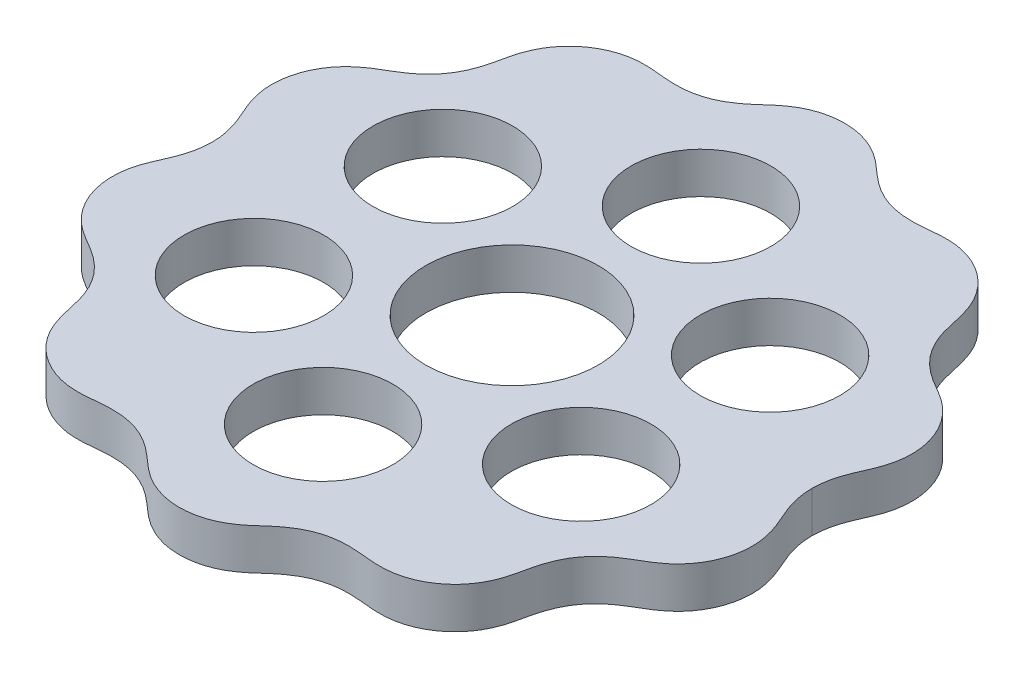
SolidWorks part; units mm, degrees
ref_plane "Front Plane" through (0, 0, 0) normal (0, 0, 1) x (1, 0, 0)
ref_plane "Top Plane" through (0, 0, 0) normal (0, 1, 0) x (1, 0, 0)
ref_plane "Right Plane" through (0, 0, 0) normal (1, 0, 0) x (0, 0, -1)
sketch "Sketch1" plane through (0, 0, 0) normal (0, 1, 0) x (1, 0, 0)
  circle A0 centre (0, 0) radius 10.5
  circle A1 centre (0, 0) radius 23 construction
  circle A2 centre (0, 23) radius 8.5
  circle A3 centre (19.9186, 11.5) radius 8.5
  circle A4 centre (19.9186, -11.5) radius 8.5
  circle A5 centre (0, -23) radius 8.5
  circle A6 centre (-19.9186, -11.5) radius 8.5
  circle A7 centre (-19.9186, 11.5) radius 8.5
  spline S0 degree 4 poles (38.858, 11.0852) (38.9322, 10.6047) (39.0099, 9.6527) (38.9421, 8.4984) (38.6357, 7.1878) (38.2864, 6.1974) (37.9882, 5.4798) (37.683, 4.7937) (37.3957, 4.1278) (37.1411, 3.4761) (36.9534, 2.9172) (36.8163, 2.4305) (36.7119, 1.9894) (36.6343, 1.5942) (36.5778, 1.2237) (36.5395, 0.8732) (36.5195, 0.614) (36.5099, 0.4402) (36.5043, 0.2856) (36.5014, 0.1595) (36.4995, 0.0195) (36.5002, -0.1092) (36.5052, -0.3492) (36.5165, -0.5716) (36.5378, -0.8544) (36.5744, -1.1968) (36.6281, -1.557) (36.7013, -1.9382) (36.7805, -2.282) (36.8613, -2.59) (36.9736, -2.9718) (37.1249, -3.4249) (37.3351, -3.9789) (37.6108, -4.6305) (37.913, -5.3088) (38.218, -6.0248) (38.5793, -7.0007) (38.9036, -8.2662) (39.0404, -9.8358) (38.8332, -11.6193) (38.3001, -13.2875) (37.487, -14.7883) (36.5194, -15.9854) (35.4632, -16.9217) (34.4806, -17.5844) (33.652, -18.0704) (32.7414, -18.5999) (31.7458, -19.2304) (30.6441, -20.104) (29.5519, -21.317) (28.7099, -22.6884) (28.1292, -24.1273) (27.764, -25.5368) (27.4986, -26.872) (27.1446, -28.2457) (26.5859, -29.6132) (25.7538, -30.9467) (24.6303, -32.1739) (23.3041, -33.1785) (21.8187, -33.928) (20.3544, -34.3562) (18.98, -34.5225) (17.8101, -34.5087) (16.8566, -34.4266) (15.9782, -34.3339) (15.1709, -34.2657) (14.1498, -34.2296) (12.9163, -34.2978) (11.4927, -34.5814) (10.0187, -35.1679) (8.7307, -35.9469) (7.6167, -36.8334) (6.6277, -37.7411) (5.5491, -38.6675) (4.2889, -39.4888) (2.8327, -40.1155) (1.2099, -40.4828) (-0.4524, -40.5514) (-2.1, -40.32) (-3.516, -39.8474) (-4.6848, -39.2366) (-5.5951, -38.6033) (-6.2913, -38.0314) (-6.9352, -37.4556) (-7.5529, -36.9053) (-8.3721, -36.2275) (-9.4173, -35.5016) (-10.7447, -34.8354) (-12.2749, -34.3962) (-13.5683, -34.2461) (-14.6093, -34.2407) (-15.4184, -34.2856) (-16.0966, -34.3467) (-16.984, -34.439) (-18.1297, -34.5342) (-19.5142, -34.4997) (-21.1001, -34.1777) (-22.6427, -33.5543) (-24.0472, -32.6623) (-25.2685, -31.5325) (-26.1543, -30.3477) (-26.7561, -29.2048) (-27.1372, -28.1922) (-27.3763, -27.3513) (-27.5642, -26.522) (-27.7363, -25.7129) (-27.9936, -24.6343) (-28.3991, -23.3794) (-29.0768, -22.0048) (-30.0541, -20.7188) (-31.0788, -19.746) (-32.0395, -19.0415) (-32.8641, -18.528) (-33.7908, -17.9899) (-34.8204, -17.3824) (-35.9613, -16.5376) (-37.0866, -15.3426) (-37.9865, -13.9433) (-38.6185, -12.4041) (-38.9637, -10.7767) (-39.0028, -9.321) (-38.8449, -8.0857) (-38.5926, -7.0813) (-38.3262, -6.297) (-38.0113, -5.5316) (-37.6749, -4.7759) (-37.3784, -4.0878) (-37.1368, -3.4613) (-36.9489, -2.8982) (-36.8252, -2.4645) (-36.7344, -2.0886) (-36.6616, -1.735) (-36.6042, -1.4037) (-36.5611, -1.0845) (-36.531, -0.7734) (-36.5136, -0.5202) (-36.5043, -0.3098) (-36.4995, -0.0654) (-36.4997, 0.0863) (-36.5054, 0.3578) (-36.5173, 0.5838) (-36.5395, 0.8738) (-36.5778, 1.2233) (-36.6343, 1.5944) (-36.7119, 1.9893) (-36.7969, 2.3486) (-36.8848, 2.6739) (-37.007, 3.0768) (-37.1717, 3.5546) (-37.3957, 4.1277) (-37.683, 4.7937) (-37.9882, 5.4798) (-38.2864, 6.1974) (-38.6357, 7.1878) (-38.9421, 8.4984) (-39.0099, 9.6527) (-38.9322, 10.6047) (-38.858, 11.0852) knots 0 0 0 0 0 0.01275 0.024998 0.030092 0.035186 0.04028 0.045374 0.049791 0.054208 0.058625 0.060834 0.063042 0.066105 0.069167 0.070698 0.07223 0.072995 0.073761 0.074526 0.075292 0.07679 0.078287 0.079785 0.081283 0.084278 0.087273 0.089361 0.091448 0.093536 0.095623 0.099798 0.103973 0.109075 0.114177 0.119279 0.124381 0.136358 0.148337 0.160314 0.171165 0.182016 0.192867 0.200455 0.208044 0.213054 0.218064 0.228085 0.238937 0.249793 0.260646 0.270064 0.279482 0.287924 0.296367 0.307217 0.318067 0.328918 0.339769 0.350619 0.36147 0.368707 0.375944 0.381255 0.386566 0.391878 0.397189 0.408044 0.418897 0.42975 0.438567 0.447383 0.456177 0.464971 0.475821 0.486672 0.497522 0.508373 0.519224 0.530074 0.536458 0.542842 0.548267 0.553691 0.559116 0.564541 0.576146 0.587 0.597853 0.606066 0.610172 0.614279 0.619103 0.623927 0.633575 0.644425 0.655276 0.666126 0.676977 0.687828 0.698679 0.70471 0.710741 0.716165 0.721589 0.727013 0.732437 0.74525 0.756105 0.766961 0.77457 0.782178 0.787304 0.792429 0.80268 0.813531 0.824381 0.835231 0.846082 0.856933 0.867783 0.873212 0.878641 0.884065 0.889489 0.894913 0.900338 0.903717 0.907097 0.910477 0.912166 0.913856 0.916569 0.919282 0.920639 0.921995 0.923352 0.924708 0.926239 0.92777 0.929302 0.930833 0.933895 0.936958 0.939166 0.941375 0.943584 0.945792 0.950209 0.954626 0.95972 0.964814 0.969908 0.975002 0.98725 1 1 1 1 1 construction
  spline S1 degree 4 poles (36.5, 0) (36.5, -0.0485) (36.5009, -0.1441) (36.5052, -0.3492) (36.5165, -0.5716) (36.5378, -0.8544) (36.5744, -1.1968) (36.6281, -1.557) (36.7013, -1.9382) (36.7805, -2.282) (36.8613, -2.59) (36.9736, -2.9718) (37.1249, -3.4249) (37.3351, -3.9789) (37.6108, -4.6305) (37.913, -5.3088) (38.218, -6.0248) (38.5793, -7.0007) (38.9036, -8.2662) (39.0404, -9.8358) (38.8332, -11.6193) (38.3001, -13.2875) (37.487, -14.7883) (36.5194, -15.9854) (35.4632, -16.9217) (34.4806, -17.5844) (33.652, -18.0704) (32.7414, -18.5999) (31.7458, -19.2304) (30.6441, -20.104) (29.5519, -21.317) (28.7099, -22.6884) (28.1292, -24.1273) (27.764, -25.5368) (27.4986, -26.872) (27.1446, -28.2457) (26.5859, -29.6132) (25.7538, -30.9467) (24.6303, -32.1739) (23.3041, -33.1785) (21.8187, -33.928) (20.3544, -34.3562) (18.98, -34.5225) (17.8101, -34.5087) (16.8566, -34.4266) (15.9782, -34.3339) (15.1709, -34.2657) (14.1498, -34.2296) (12.9163, -34.2978) (11.4927, -34.5814) (10.0187, -35.1679) (8.7307, -35.9469) (7.6167, -36.8334) (6.6277, -37.7411) (5.5491, -38.6675) (4.2889, -39.4888) (2.8327, -40.1155) (1.2099, -40.4828) (-0.4524, -40.5514) (-2.1, -40.32) (-3.516, -39.8474) (-4.6848, -39.2366) (-5.5951, -38.6033) (-6.2913, -38.0314) (-6.9352, -37.4556) (-7.5529, -36.9053) (-8.3721, -36.2275) (-9.4173, -35.5016) (-10.7447, -34.8354) (-12.2749, -34.3962) (-13.5683, -34.2461) (-14.6093, -34.2407) (-15.4184, -34.2856) (-16.0966, -34.3467) (-16.984, -34.439) (-18.1297, -34.5342) (-19.5142, -34.4997) (-21.1001, -34.1777) (-22.6427, -33.5543) (-24.0472, -32.6623) (-25.2685, -31.5325) (-26.1543, -30.3477) (-26.7561, -29.2048) (-27.1372, -28.1922) (-27.3763, -27.3513) (-27.5642, -26.522) (-27.7363, -25.7129) (-27.9936, -24.6343) (-28.3991, -23.3794) (-29.0768, -22.0048) (-30.0541, -20.7188) (-31.0788, -19.746) (-32.0395, -19.0415) (-32.8641, -18.528) (-33.7908, -17.9899) (-34.8204, -17.3824) (-35.9613, -16.5376) (-37.0866, -15.3426) (-37.9865, -13.9433) (-38.6185, -12.4041) (-38.9637, -10.7767) (-39.0028, -9.321) (-38.8449, -8.0857) (-38.5926, -7.0813) (-38.3262, -6.297) (-38.0113, -5.5316) (-37.6749, -4.7759) (-37.3784, -4.0878) (-37.1368, -3.4613) (-36.9489, -2.8982) (-36.8252, -2.4645) (-36.7344, -2.0886) (-36.6616, -1.735) (-36.6042, -1.4037) (-36.5611, -1.0845) (-36.531, -0.7734) (-36.5136, -0.5202) (-36.5043, -0.3098) (-36.5008, -0.1322) (-36.5, -0.0439) (-36.5, 0) knots 0.075292 0.075292 0.075292 0.075292 0.075292 0.07679 0.078287 0.079785 0.081283 0.084278 0.087273 0.089361 0.091448 0.093536 0.095623 0.099798 0.103973 0.109075 0.114177 0.119279 0.124381 0.136358 0.148337 0.160314 0.171165 0.182016 0.192867 0.200455 0.208044 0.213054 0.218064 0.228085 0.238937 0.249793 0.260646 0.270064 0.279482 0.287924 0.296367 0.307217 0.318067 0.328918 0.339769 0.350619 0.36147 0.368707 0.375944 0.381255 0.386566 0.391878 0.397189 0.408044 0.418897 0.42975 0.438567 0.447383 0.456177 0.464971 0.475821 0.486672 0.497522 0.508373 0.519224 0.530074 0.536458 0.542842 0.548267 0.553691 0.559116 0.564541 0.576146 0.587 0.597853 0.606066 0.610172 0.614279 0.619103 0.623927 0.633575 0.644425 0.655276 0.666126 0.676977 0.687828 0.698679 0.70471 0.710741 0.716165 0.721589 0.727013 0.732437 0.74525 0.756105 0.766961 0.77457 0.782178 0.787304 0.792429 0.80268 0.813531 0.824381 0.835231 0.846082 0.856933 0.867783 0.873212 0.878641 0.884065 0.889489 0.894913 0.900338 0.903717 0.907097 0.910477 0.912166 0.913856 0.916569 0.919282 0.920639 0.921995 0.923352 0.924708 0.924708 0.924708 0.924708 0.924708
  spline S2 degree 4 poles (-38.858, -11.0852) (-38.9322, -10.6047) (-39.0099, -9.6527) (-38.9421, -8.4984) (-38.6357, -7.1878) (-38.2864, -6.1974) (-37.9882, -5.4798) (-37.683, -4.7937) (-37.3957, -4.1277) (-37.1717, -3.5546) (-37.007, -3.0768) (-36.8848, -2.6739) (-36.7969, -2.3487) (-36.7119, -1.9892) (-36.6456, -1.652) (-36.5953, -1.3382) (-36.5586, -1.0489) (-36.535, -0.8153) (-36.5195, -0.614) (-36.5099, -0.4403) (-36.5043, -0.2858) (-36.5014, -0.1597) (-36.4995, -0.0193) (-36.5001, 0.0875) (-36.5031, 0.2488) (-36.5095, 0.4308) (-36.5187, 0.6009) (-36.5378, 0.8538) (-36.5744, 1.1972) (-36.6281, 1.5568) (-36.7013, 1.9383) (-36.7983, 2.3595) (-36.9244, 2.8204) (-37.0966, 3.3504) (-37.3351, 3.9789) (-37.6108, 4.6304) (-37.913, 5.3088) (-38.218, 6.0248) (-38.5793, 7.0007) (-38.9036, 8.2662) (-39.0404, 9.8358) (-38.8332, 11.6193) (-38.3001, 13.2875) (-37.487, 14.7883) (-36.5194, 15.9854) (-35.4632, 16.9217) (-34.4806, 17.5844) (-33.652, 18.0704) (-32.9065, 18.5039) (-32.257, 18.9066) (-31.4454, 19.4687) (-30.5156, 20.2467) (-29.5519, 21.317) (-28.7099, 22.6884) (-28.1292, 24.1273) (-27.764, 25.5368) (-27.4986, 26.872) (-27.1446, 28.2457) (-26.5859, 29.6132) (-25.7538, 30.9467) (-24.6303, 32.1739) (-23.3041, 33.1785) (-21.8187, 33.928) (-20.3544, 34.3562) (-18.98, 34.5225) (-17.8101, 34.5087) (-16.8566, 34.4266) (-15.9782, 34.3339) (-15.1709, 34.2657) (-14.1498, 34.2296) (-12.9163, 34.2978) (-11.4927, 34.5814) (-10.0187, 35.1679) (-8.7307, 35.9469) (-7.6167, 36.8334) (-6.6277, 37.7411) (-5.5491, 38.6675) (-4.2889, 39.4888) (-2.8327, 40.1155) (-1.2099, 40.4828) (0.4524, 40.5514) (2.1, 40.32) (3.516, 39.8474) (4.6848, 39.2366) (5.5951, 38.6033) (6.2913, 38.0314) (6.9352, 37.4556) (7.5529, 36.9053) (8.3721, 36.2275) (9.4173, 35.5016) (10.7447, 34.8354) (12.2749, 34.3962) (13.5683, 34.2461) (14.6093, 34.2407) (15.4184, 34.2856) (16.0966, 34.3467) (16.984, 34.439) (18.1297, 34.5342) (19.5142, 34.4997) (21.1001, 34.1777) (22.6427, 33.5543) (24.0472, 32.6623) (25.2685, 31.5325) (26.1543, 30.3477) (26.7561, 29.2048) (27.1372, 28.1922) (27.3763, 27.3513) (27.5642, 26.522) (27.7363, 25.7129) (27.9936, 24.6343) (28.3991, 23.3794) (29.0768, 22.0048) (30.0541, 20.7188) (31.0788, 19.746) (32.0395, 19.0415) (32.8641, 18.528) (33.7908, 17.9899) (34.8204, 17.3824) (35.9613, 16.5376) (37.0866, 15.3426) (37.9865, 13.9433) (38.6185, 12.4041) (38.9637, 10.7767) (39.0028, 9.321) (38.8449, 8.0857) (38.5926, 7.0813) (38.3262, 6.297) (38.0113, 5.5316) (37.6749, 4.7759) (37.3784, 4.0878) (37.1368, 3.4612) (36.9693, 2.9594) (36.8606, 2.5884) (36.7798, 2.2765) (36.7214, 2.0254) (36.6616, 1.735) (36.6042, 1.4036) (36.5611, 1.0847) (36.531, 0.7731) (36.5153, 0.5458) (36.5078, 0.3885) (36.5025, 0.222) (36.5, 0.0774) (36.4996, -0.0243) (36.5014, -0.1598) (36.5043, -0.2859) (36.5099, -0.4403) (36.5195, -0.614) (36.535, -0.8153) (36.5586, -1.0489) (36.5953, -1.3382) (36.6455, -1.652) (36.7119, -1.9892) (36.8163, -2.4307) (36.9534, -2.9171) (37.1411, -3.4761) (37.3957, -4.1277) (37.683, -4.7937) (37.9882, -5.4798) (38.2864, -6.1974) (38.6357, -7.1878) (38.9421, -8.4984) (39.0099, -9.6527) (38.9322, -10.6047) (38.858, -11.0852) knots 0 0 0 0 0 0.01275 0.024998 0.030092 0.035186 0.04028 0.045374 0.049791 0.054208 0.056416 0.058625 0.060834 0.063042 0.066105 0.067636 0.069167 0.070698 0.07223 0.072995 0.073761 0.074526 0.075292 0.07679 0.077538 0.078287 0.079785 0.081283 0.084278 0.087273 0.089361 0.091448 0.095623 0.099798 0.103973 0.109075 0.114177 0.119279 0.124381 0.136358 0.148337 0.160314 0.171165 0.182016 0.192867 0.200455 0.208044 0.213054 0.218064 0.223074 0.228085 0.238937 0.249793 0.260646 0.270064 0.279482 0.287924 0.296367 0.307217 0.318067 0.328918 0.339769 0.350619 0.36147 0.368707 0.375944 0.381255 0.386566 0.391878 0.397189 0.408044 0.418897 0.42975 0.438567 0.447383 0.456177 0.464971 0.475821 0.486672 0.497522 0.508373 0.519224 0.530074 0.536458 0.542842 0.548267 0.553691 0.559116 0.564541 0.576146 0.587 0.597853 0.606066 0.610172 0.614279 0.619103 0.623927 0.633575 0.644425 0.655276 0.666126 0.676977 0.687828 0.698679 0.70471 0.710741 0.716165 0.721589 0.727013 0.732437 0.74525 0.756105 0.766961 0.77457 0.782178 0.787304 0.792429 0.80268 0.813531 0.824381 0.835231 0.846082 0.856933 0.867783 0.873212 0.878641 0.884065 0.889489 0.894913 0.900338 0.903717 0.907097 0.908787 0.910477 0.912166 0.913856 0.916569 0.919282 0.920639 0.921995 0.922673 0.923352 0.924708 0.925474 0.926239 0.927005 0.92777 0.929302 0.930833 0.932364 0.933895 0.936958 0.939166 0.941375 0.945792 0.950209 0.954626 0.95972 0.964814 0.969908 0.975002 0.98725 1 1 1 1 1 construction
  spline S3 degree 4 poles (-36.5, 0) (-36.5, 0.0485) (-36.5007, 0.1203) (-36.5031, 0.2488) (-36.5095, 0.4308) (-36.5187, 0.6009) (-36.5378, 0.8538) (-36.5744, 1.1972) (-36.6281, 1.5568) (-36.7013, 1.9383) (-36.7983, 2.3595) (-36.9244, 2.8204) (-37.0966, 3.3504) (-37.3351, 3.9789) (-37.6108, 4.6304) (-37.913, 5.3088) (-38.218, 6.0248) (-38.5793, 7.0007) (-38.9036, 8.2662) (-39.0404, 9.8358) (-38.8332, 11.6193) (-38.3001, 13.2875) (-37.487, 14.7883) (-36.5194, 15.9854) (-35.4632, 16.9217) (-34.4806, 17.5844) (-33.652, 18.0704) (-32.9065, 18.5039) (-32.257, 18.9066) (-31.4454, 19.4687) (-30.5156, 20.2467) (-29.5519, 21.317) (-28.7099, 22.6884) (-28.1292, 24.1273) (-27.764, 25.5368) (-27.4986, 26.872) (-27.1446, 28.2457) (-26.5859, 29.6132) (-25.7538, 30.9467) (-24.6303, 32.1739) (-23.3041, 33.1785) (-21.8187, 33.928) (-20.3544, 34.3562) (-18.98, 34.5225) (-17.8101, 34.5087) (-16.8566, 34.4266) (-15.9782, 34.3339) (-15.1709, 34.2657) (-14.1498, 34.2296) (-12.9163, 34.2978) (-11.4927, 34.5814) (-10.0187, 35.1679) (-8.7307, 35.9469) (-7.6167, 36.8334) (-6.6277, 37.7411) (-5.5491, 38.6675) (-4.2889, 39.4888) (-2.8327, 40.1155) (-1.2099, 40.4828) (0.4524, 40.5514) (2.1, 40.32) (3.516, 39.8474) (4.6848, 39.2366) (5.5951, 38.6033) (6.2913, 38.0314) (6.9352, 37.4556) (7.5529, 36.9053) (8.3721, 36.2275) (9.4173, 35.5016) (10.7447, 34.8354) (12.2749, 34.3962) (13.5683, 34.2461) (14.6093, 34.2407) (15.4184, 34.2856) (16.0966, 34.3467) (16.984, 34.439) (18.1297, 34.5342) (19.5142, 34.4997) (21.1001, 34.1777) (22.6427, 33.5543) (24.0472, 32.6623) (25.2685, 31.5325) (26.1543, 30.3477) (26.7561, 29.2048) (27.1372, 28.1922) (27.3763, 27.3513) (27.5642, 26.522) (27.7363, 25.7129) (27.9936, 24.6343) (28.3991, 23.3794) (29.0768, 22.0048) (30.0541, 20.7188) (31.0788, 19.746) (32.0395, 19.0415) (32.8641, 18.528) (33.7908, 17.9899) (34.8204, 17.3824) (35.9613, 16.5376) (37.0866, 15.3426) (37.9865, 13.9433) (38.6185, 12.4041) (38.9637, 10.7767) (39.0028, 9.321) (38.8449, 8.0857) (38.5926, 7.0813) (38.3262, 6.297) (38.0113, 5.5316) (37.6749, 4.7759) (37.3784, 4.0878) (37.1368, 3.4612) (36.9693, 2.9594) (36.8606, 2.5884) (36.7798, 2.2765) (36.7214, 2.0254) (36.6616, 1.735) (36.6042, 1.4036) (36.5611, 1.0847) (36.531, 0.7731) (36.5153, 0.5458) (36.5078, 0.3885) (36.5025, 0.222) (36.5006, 0.1092) (36.5, 0.0439) (36.5, 0) knots 0.075292 0.075292 0.075292 0.075292 0.075292 0.07679 0.077538 0.078287 0.079785 0.081283 0.084278 0.087273 0.089361 0.091448 0.095623 0.099798 0.103973 0.109075 0.114177 0.119279 0.124381 0.136358 0.148337 0.160314 0.171165 0.182016 0.192867 0.200455 0.208044 0.213054 0.218064 0.223074 0.228085 0.238937 0.249793 0.260646 0.270064 0.279482 0.287924 0.296367 0.307217 0.318067 0.328918 0.339769 0.350619 0.36147 0.368707 0.375944 0.381255 0.386566 0.391878 0.397189 0.408044 0.418897 0.42975 0.438567 0.447383 0.456177 0.464971 0.475821 0.486672 0.497522 0.508373 0.519224 0.530074 0.536458 0.542842 0.548267 0.553691 0.559116 0.564541 0.576146 0.587 0.597853 0.606066 0.610172 0.614279 0.619103 0.623927 0.633575 0.644425 0.655276 0.666126 0.676977 0.687828 0.698679 0.70471 0.710741 0.716165 0.721589 0.727013 0.732437 0.74525 0.756105 0.766961 0.77457 0.782178 0.787304 0.792429 0.80268 0.813531 0.824381 0.835231 0.846082 0.856933 0.867783 0.873212 0.878641 0.884065 0.889489 0.894913 0.900338 0.903717 0.907097 0.908787 0.910477 0.912166 0.913856 0.916569 0.919282 0.920639 0.921995 0.922673 0.923352 0.924708 0.924708 0.924708 0.924708 0.924708
  point P24 (0, 0)
  dimension "D1" = 21
  dimension "D2" = 17
  dimension "D4" = 46
  dimension "D3" = 6
extrude "Boss-Extrude1" add sketch "Sketch1" along normal blind 5
